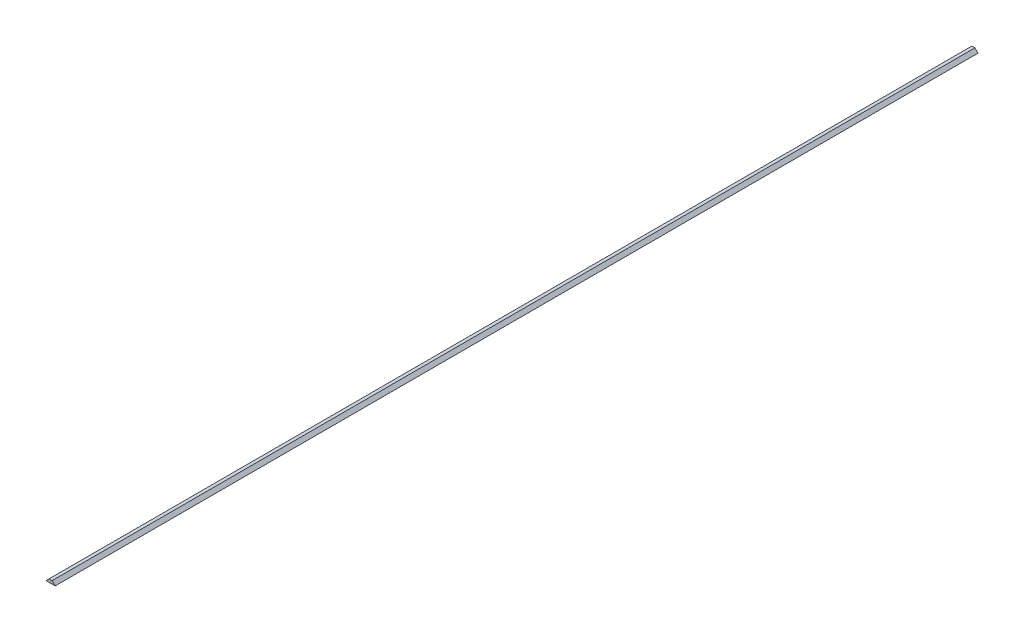
SolidWorks part; units mm, degrees
ref_plane "Front Plane" through (0, 0, 0) normal (0, 0, 1) x (1, 0, 0)
ref_plane "Top Plane" through (0, 0, 0) normal (0, 1, 0) x (1, 0, 0)
ref_plane "Right Plane" through (0, 0, 0) normal (1, 0, 0) x (0, 0, -1)
sketch "Sketch1" plane through (0, 0, 0) normal (0, 0, 1) x (1, 0, 0)
  line L0 (-15, 0) -> (15, 0)
  line L1 (15, 0) -> (5, 10)
  line L2 (5, 10) -> (-5, 10)
  line L3 (-5, 10) -> (-15, 0)
  line L4 (0, 0) -> (0, 17.9305) construction
  point P4 (0, 0)
  dimension "D1" = 30
  dimension "D2" = 10
  dimension "D3" = 45
extrude "Boss-Extrude1" add sketch "Sketch1" along normal blind 3000
